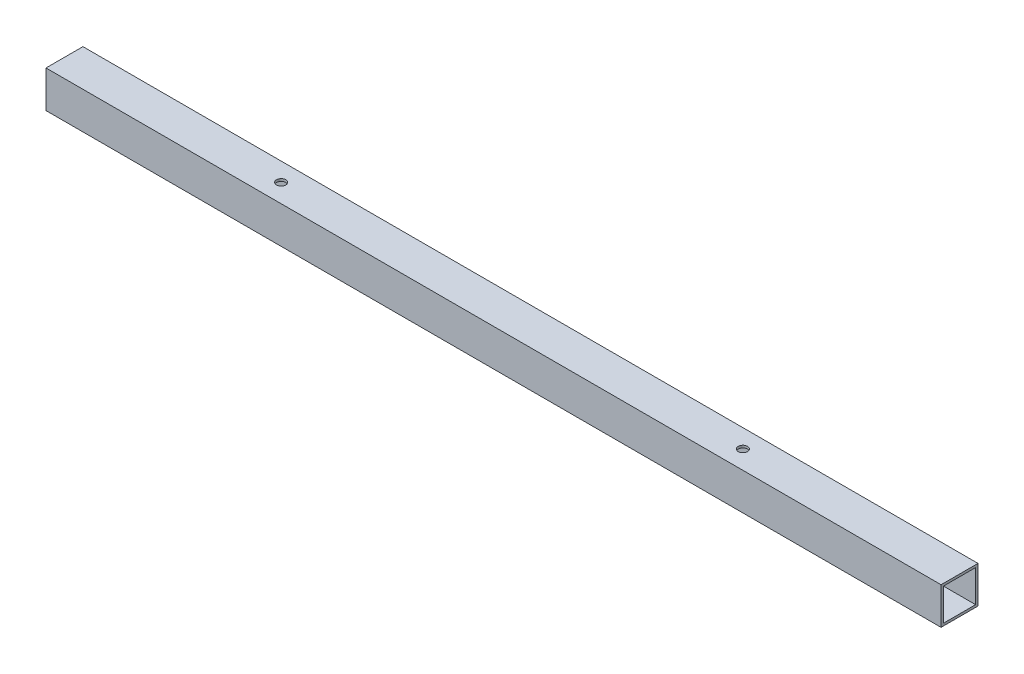
SolidWorks part; units mm, degrees
material "AISI 1020"
ref_plane "Front Plane" through (0, 0, 0) normal (0, 0, 1) x (1, 0, 0)
ref_plane "Top Plane" through (0, 0, 0) normal (0, 1, 0) x (1, 0, 0)
ref_plane "Right Plane" through (0, 0, 0) normal (1, 0, 0) x (0, 0, -1)
sketch "Sketch1" plane through (0, 0, 0) normal (0, 1, 0) x (1, 0, 0)
  line L0 (0, 0) -> (615.4, 0)
  dimension "D1" = 615.4
other "Al tube square AL TUBE 1 SQR X 0.065 WALL(1)"
ref_plane "Plane2" through (0, 0, 0) normal (1, 0, 0) x (0, 0, -1)
sketch "Sketch16" plane through (0, 0, 0) normal (1, 0, 0) x (0, 0, -1)
  line L0 (-11.049, -11.049) -> (-11.049, 11.049)
  line L1 (11.049, 11.049) -> (-11.049, 11.049)
  line L2 (11.049, 11.049) -> (11.049, -11.049)
  line L3 (-11.049, -11.049) -> (11.049, -11.049)
  line L4 (-12.7, -12.7) -> (12.7, -12.7)
  line L5 (-12.7, -12.7) -> (-12.7, 12.7)
  line L6 (12.7, 12.7) -> (-12.7, 12.7)
  line L7 (12.7, 12.7) -> (12.7, -12.7)
  line L8 (0, -11.049) -> (0, -12.7) construction
  line L9 (0, -11.049) -> (0, 11.049) construction
  line L10 (0, 11.049) -> (0, 12.7) construction
  line L11 (12.7, 0) -> (11.049, 0) construction
  line L12 (11.049, 0) -> (-11.049, 0) construction
  line L13 (-11.049, 0) -> (-12.7, 0) construction
  point P14 (0, 0)
  point P17 (0, 0)
  dimension "Thickness" = 1.651
  dimension "V_leg" = 25.4
  dimension "H_leg" = 25.4
sketch "Sketch17" plane through (0, 12.7, 0) normal (0, 1, 0) x (1, 0, 0)
  line L0 (307.7, 12.7) -> (307.7, -12.7) construction
  line L1 (615.4, 12.7) -> (0, 12.7) construction
  line L2 (615.4, -12.7) -> (0, -12.7) construction
  line L3 (0, 0) -> (615.4, 0) construction
  line L4 (615.4, 12.7) -> (615.4, -12.7) construction
  point P11 (148.95, 0)
  point P12 (466.45, 0)
  dimension "D1" = 158.75
hole_wizard "1/4 (0.25) Diameter Hole1" positions "Sketch17" profile "Sketch18" hole size "1/4" standard "ANSI Inch" end condition through all
sketch "Sketch18" plane through (466.45, 12.7, 0) normal (1, 0, 0) x (0, 0, 1)
  line L0 (0, 0) -> (0, 25.4)
  line L1 (0, 25.4) -> (3.175, 25.4)
  line L2 (3.175, 25.4) -> (3.175, 0)
  line L5 (3.175, 0) -> (0, 0)
  line L11 (0, -6.35) -> (0, 107.95) construction
  dimension "Thru Hole Dia." = 6.35
  dimension "Thru Hole Depth" = 25.4
equation "\"D1@Sketch17\"=(17.5in/2)-2.5in"
